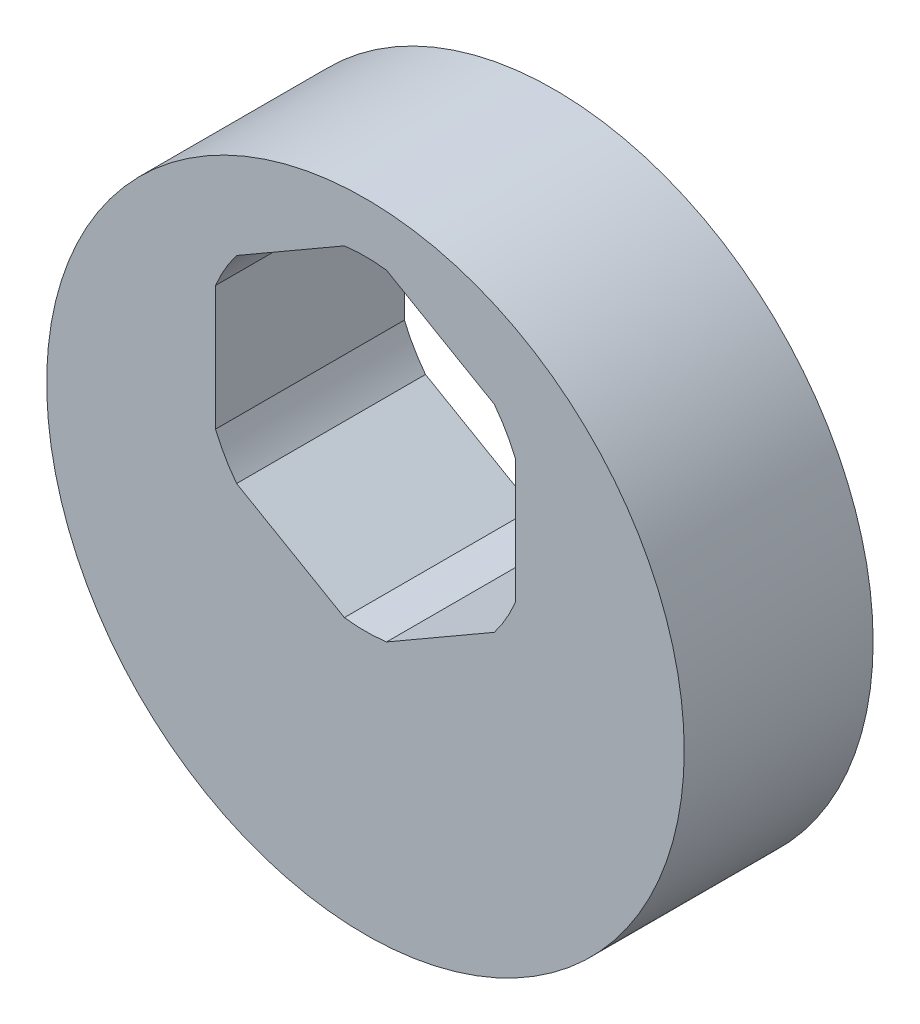
SolidWorks part; units mm, degrees
material "PE High Density"
ref_plane "Front Plane" through (0, 0, 0) normal (0, 0, 1) x (1, 0, 0)
ref_plane "Top Plane" through (0, 0, 0) normal (0, 1, 0) x (1, 0, 0)
ref_plane "Right Plane" through (0, 0, 0) normal (1, 0, 0) x (0, 0, -1)
sketch "Sketch1" plane through (0, 0, 0) normal (0, 0, 1) x (1, 0, 0)
  circle A0 centre (0, 0) radius 13.5
  dimension "D1" = 27
extrude "Boss-Extrude1" add sketch "Sketch1" along normal mid plane 8
sketch "Sketch2" plane through (0, 0, 4) normal (0, 0, 1) x (1, 0, 0)
  line L0 (0, 0) -> (0, 4.5) construction
  line L1 (-0.893, 11.3168) -> (-5.457, 8.6818)
  line L2 (-6.35, 7.135) -> (-6.35, 1.865)
  line L3 (-5.457, 0.3182) -> (-0.893, -2.3168)
  line L4 (0.893, -2.3168) -> (5.457, 0.3182)
  line L5 (6.35, 1.865) -> (6.35, 7.135)
  line L6 (5.457, 8.6818) -> (0.893, 11.3168)
  line L7 (-6.35, 8.1662) -> (-6.35, 7.135) construction
  line L8 (-5.457, 8.6818) -> (-6.35, 8.1662) construction
  line L9 (0.893, 11.3168) -> (0, 11.8323) construction
  line L10 (0, 11.8323) -> (-0.893, 11.3168) construction
  line L11 (6.35, 8.1662) -> (5.457, 8.6818) construction
  line L12 (6.35, 7.135) -> (6.35, 8.1662) construction
  line L13 (6.35, 0.8338) -> (6.35, 1.865) construction
  line L14 (5.457, 0.3182) -> (6.35, 0.8338) construction
  line L15 (0, -2.8323) -> (0.893, -2.3168) construction
  line L16 (-0.893, -2.3168) -> (0, -2.8323) construction
  line L17 (-6.35, 0.8338) -> (-5.457, 0.3182) construction
  line L18 (-6.35, 1.865) -> (-6.35, 0.8338) construction
  circle A0 centre (0, 4.5) radius 6.35 construction
  arc A1 (-5.457, 8.6818) -> (-6.35, 7.135) centre (0, 4.5) ccw
  arc A2 (0.893, 11.3168) -> (-0.893, 11.3168) centre (0, 4.5) ccw
  arc A3 (6.35, 7.135) -> (5.457, 8.6818) centre (0, 4.5) ccw
  arc A4 (5.457, 0.3182) -> (6.35, 1.865) centre (0, 4.5) ccw
  arc A5 (-0.893, -2.3168) -> (0.893, -2.3168) centre (0, 4.5) ccw
  arc A6 (-6.35, 1.865) -> (-5.457, 0.3182) centre (0, 4.5) ccw
  circle A7 centre (0, 0) radius 13.5 construction
  point P22 (0, 13.5)
  point P23 (0, 11.7762)
  dimension "D3" = 13.75
  dimension "D1" = 12.7
  dimension "D2" = 4.5
extrude "Cut-Extrude1" cut sketch "Sketch2" against normal through all
